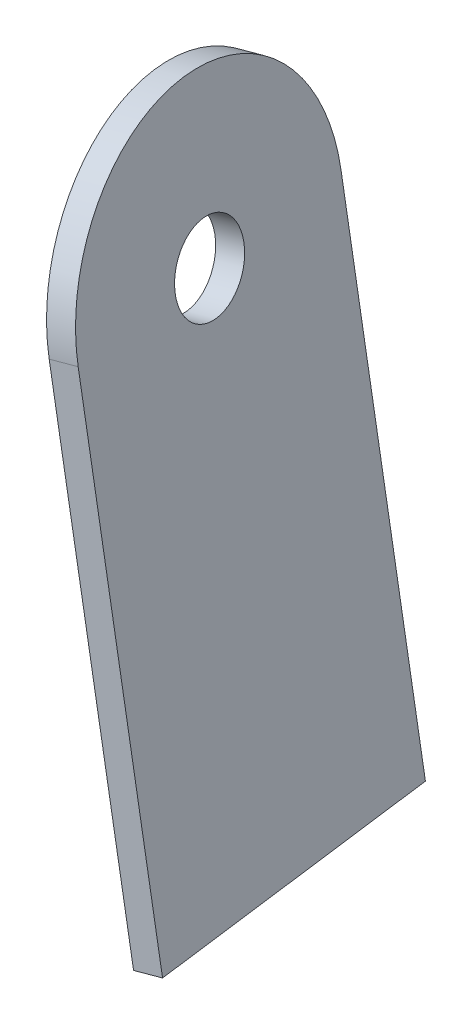
SolidWorks part; units mm, degrees
ref_plane "Front Plane" through (0, 0, 0) normal (0, 0, 1) x (1, 0, 0)
ref_plane "Top Plane" through (0, 0, 0) normal (0, 1, 0) x (1, 0, 0)
ref_plane "Right Plane" through (0, 0, 0) normal (1, 0, 0) x (0, 0, -1)
ref_plane "Plane1" through (-406.8367, 67.8624, -60.1148) normal (0.9761, -0.1628, 0.1442) x (-0.152, -0.0366, 0.9877)
sketch "Sketch2" plane through (-406.8367, 67.8624, -60.1148) normal (0.9761, -0.1628, 0.1442) x (-0.152, -0.0366, 0.9877)
  line L0 (-544.7858, 305.6554) -> (-546.4574, 275.2213)
  line L1 (-74.0304, 279.7982) -> (-708.5122, 314.6484) construction
  line L2 (-527.4361, 274.1765) -> (-525.7645, 304.6106)
  line L3 (-525.7645, 304.6106) -> (-544.7858, 305.6554)
  line L4 (-536.7928, 277.5014) -> (-537.1007, 271.8964) construction
  arc A0 (-546.4574, 275.2213) -> (-527.4361, 274.1765) centre (-536.9468, 274.6989) ccw
  circle A1 centre (-536.9468, 274.6989) radius 2.4892
  dimension "D1" = 9.525
  dimension "D2" = 4.9784
  dimension "D3" = 19.05
  dimension "D4" = 30.48
extrude "Boss-Extrude1" add sketch "Sketch2" along normal blind 1.5875
mirror "Mirror2" about plane through (0, 0, 0) normal (1, 0, 0) of bodies 101
delete or keep bodies "Body-Delete/Keep 1" type delete bodies bodies 101
